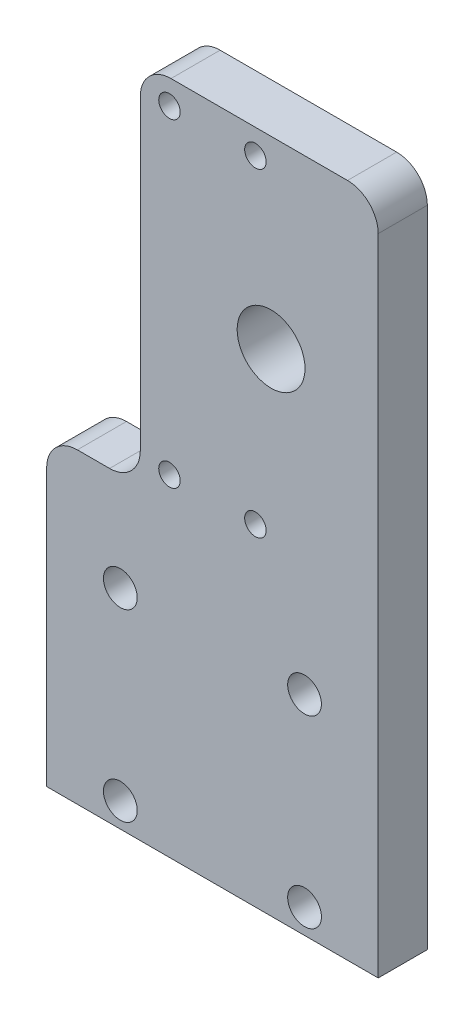
SolidWorks part; units mm, degrees
ref_plane "前视基准面" through (0, 0, 0) normal (0, 0, 1) x (1, 0, 0)
ref_plane "上视基准面" through (0, 0, 0) normal (0, 1, 0) x (1, 0, 0)
ref_plane "右视基准面" through (0, 0, 0) normal (1, 0, 0) x (0, 0, -1)
other "Configuration Table"
sketch "草图1" plane through (0, 0, 0) normal (0, 0, 1) x (1, 0, 0)
  line L0 (27, -110) -> (27, -10) construction
  line L1 (0, 0) -> (54, 0)
  line L2 (0, 0) -> (0, -110)
  line L3 (0, -110) -> (54, -110)
  line L4 (54, -52) -> (54, -110)
  line L9 (54, -52) -> (54, 0)
  circle A0 centre (12, -106) radius 2.75
  circle A1 centre (42, -106) radius 2.75
  circle A2 centre (42, -76) radius 2.75
  circle A3 centre (12, -76) radius 2.75
  dimension "D7" = 5.5
  dimension "D1" = 54
  dimension "D2" = 110
  dimension "D5" = 54
  dimension "D6" = 4
  dimension "D8" = 15
  dimension "D9" = 2
  dimension "D10" = 2
extrude "凸台-拉伸1" add sketch "草图1" along normal blind 8
sketch "草图2" plane through (0, 0, 0) normal (0, 0, -1) x (-1, 0, 0)
  line L0 (-27, 0) -> (-27, -110) construction
  line L1 (-54, 0) -> (0, 0) construction
  line L2 (0, -110) -> (-54, -110) construction
  line L3 (-15.25, 0) -> (-15.25, -60)
  line L4 (-15.25, -60) -> (0, -60)
  line L5 (0, 0) -> (0, -110) construction
  line L6 (-15.25, 0) -> (0, 0)
  line L7 (0, 0) -> (0, -60)
  dimension "D1" = 11.75
  dimension "D2" = 60
extrude "切除-拉伸1" cut sketch "草图2" against normal blind 10
fillet "圆角1" radius 5 4 edges at (15.25, 0, 4) (15.25, -60, 4) (54, 0, 4) (0, -60, 4)
sketch "草图3" plane through (0, 0, 0) normal (0, 0, -1) x (-1, 0, 0)
  circle A0 centre (-20, -4) radius 1.75
  circle A1 centre (-34, -4) radius 1.75
  circle A2 centre (-34, -56) radius 1.75
  circle A3 centre (-20, -56) radius 1.75
  dimension "D1" = 3.5
  dimension "D2" = 2
  dimension "D3" = 2
extrude "切除-拉伸2" cut sketch "草图3" against normal through all
sketch "草图4" plane through (0, 0, 0) normal (0, 0, -1) x (-1, 0, 0)
  line L0 (-15.25, -5) -> (-15.25, -55) construction
  line L1 (-49, 0) -> (-20.25, 0) construction
  circle A0 centre (-36.55, -30) radius 5.525
  dimension "D2" = 11.05
  dimension "D1" = 21.3
  dimension "D3" = 30
extrude "切除-拉伸3" cut sketch "草图4" against normal blind 10
